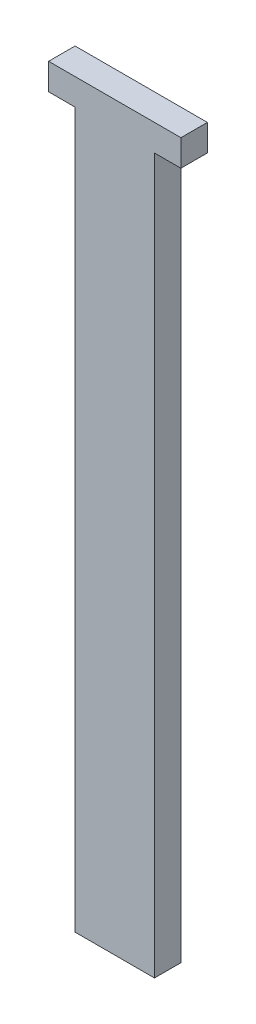
SolidWorks part; units mm, degrees
ref_plane "Front Plane" through (0, 0, 0) normal (0, 0, 1) x (1, 0, 0)
ref_plane "Top Plane" through (0, 0, 0) normal (0, 1, 0) x (1, 0, 0)
ref_plane "Right Plane" through (0, 0, 0) normal (1, 0, 0) x (0, 0, -1)
sketch "Sketch1" plane through (0, 0, 0) normal (0, 0, 1) x (1, 0, 0)
  line L0 (-12.5192, 47.7885) -> (-7.5192, 47.7885)
  line L2 (-27.5192, 47.7885) -> (-27.5192, -87.2115)
  line L3 (-27.5192, -87.2115) -> (-12.5192, -87.2115)
  line L4 (-12.5192, 47.7885) -> (-12.5192, -87.2115)
  line L5 (-32.5192, 52.7885) -> (-7.5192, 52.7885)
  line L6 (-32.5192, 52.7885) -> (-32.5192, 47.7885)
  line L7 (-32.5192, 47.7885) -> (-27.5192, 47.7885)
  line L8 (-7.5192, 52.7885) -> (-7.5192, 47.7885)
  point P8 (-20.0192, 52.7885)
  point P9 (-20.0192, -87.2115)
  dimension "D1" = 135
  dimension "D2" = 15
  dimension "D3" = 25
  dimension "D4" = 5
extrude "Boss-Extrude1" add sketch "Sketch1" along normal blind 5
